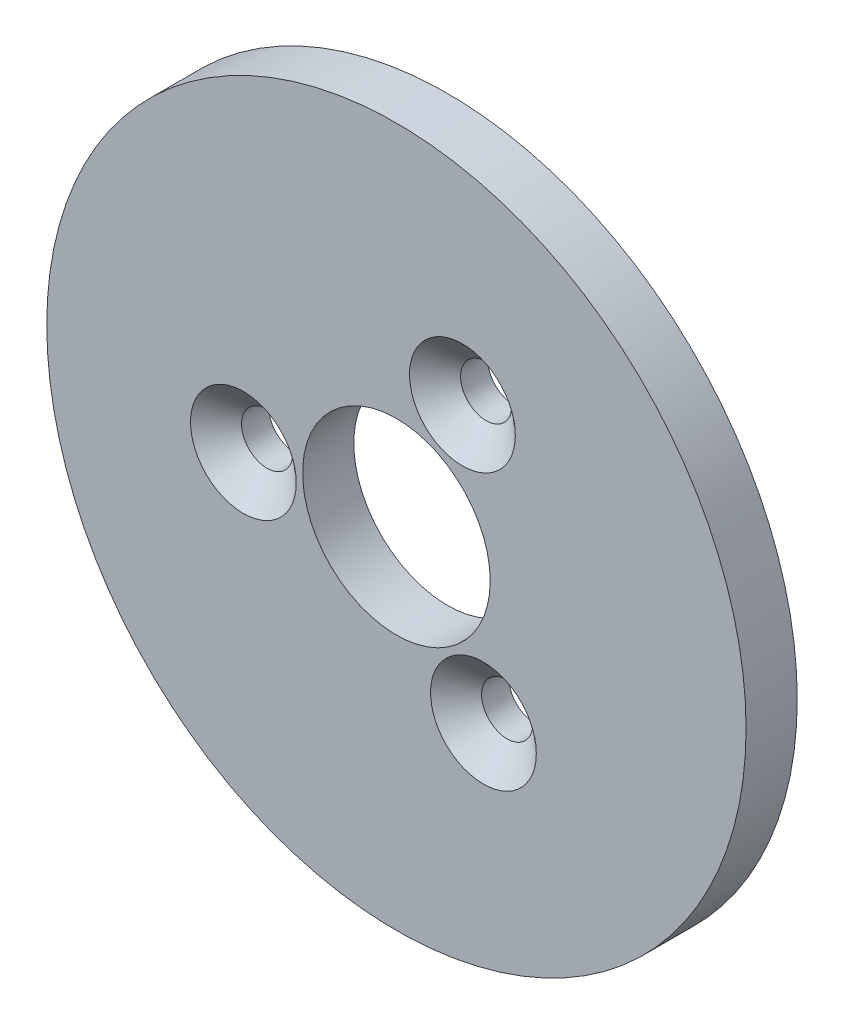
SolidWorks part; units mm, degrees
material "Acrylic (Medium-high impact)"
ref_plane "Front Plane" through (0, 0, 0) normal (0, 0, 1) x (1, 0, 0)
ref_plane "Top Plane" through (0, 0, 0) normal (0, 1, 0) x (1, 0, 0)
ref_plane "Right Plane" through (0, 0, 0) normal (1, 0, 0) x (0, 0, -1)
sketch "Sketch1" plane through (0, 0, 0) normal (0, 0, 1) x (1, 0, 0)
  circle A0 centre (0, 0) radius 20.5
  dimension "D1" = 41
extrude "Boss-Extrude1" add sketch "Sketch1" along normal blind 3
sketch "Sketch2" plane through (0, 0, 3) normal (0, 0, 1) x (1, 0, 0)
  circle A3 centre (-8.9719, -0.7111) radius 1.5
  circle A4 centre (-8.9719, -0.7111) radius 1.5
  circle A5 centre (5.1018, -7.4143) radius 1.5
  circle A6 centre (5.1018, -7.4143) radius 1.5
  circle A7 centre (3.8701, 8.1254) radius 1.5
  circle A8 centre (3.8701, 8.1254) radius 1.5
  dimension "D2" = 0
  dimension "D3" = 0
  dimension "D4" = 0
extrude "Cut-Extrude1" cut sketch "Sketch2" against normal through all
chamfer "Chamfer1" distance 1.6 angle 41 3 edges at (-7.4719, -0.7111, 3) (5.3701, 8.1254, 3) (6.6018, -7.4143, 3)
sketch "Sketch3" plane through (0, 0, 3) normal (0, 0, 1) x (1, 0, 0)
  circle A1 centre (0, 0) radius 5.5
  circle A2 centre (0, 0) radius 5.5
  dimension "D1" = 0
extrude "Cut-Extrude2" cut sketch "Sketch3" against normal through all
equation "\"smallPulleyTeeth\"= 30"
equation "\"largePulleyTeeth\"= 30"
equation "\"eighthThick\"= 3.0mm"
equation "\"sixteenthThick\" = 1.7mm"
equation "\"quarterThick\"=6.0mm"
equation "\"OD\" = 145mm"
equation "\"puckAngle\" = 60.5deg"
equation "\"puckDiam\" = 76.5mm"
equation "\"axlePress\" = 5.9mm"
equation "\"press\" = 0.2mm"
equation "\"wheelClear\" = 0.3mm"
equation "\"10-32clear\" = 4.8mm"
equation "\"D1@Boss-Extrude1\"=\"eighthThick\""
equation "\"D1@Chamfer1\"=(6.5-\"6-32clear\")/2"
equation "\"6-32clear\" = 3.3mm"
equation "\"8-32clear\" = 4.0mm"
